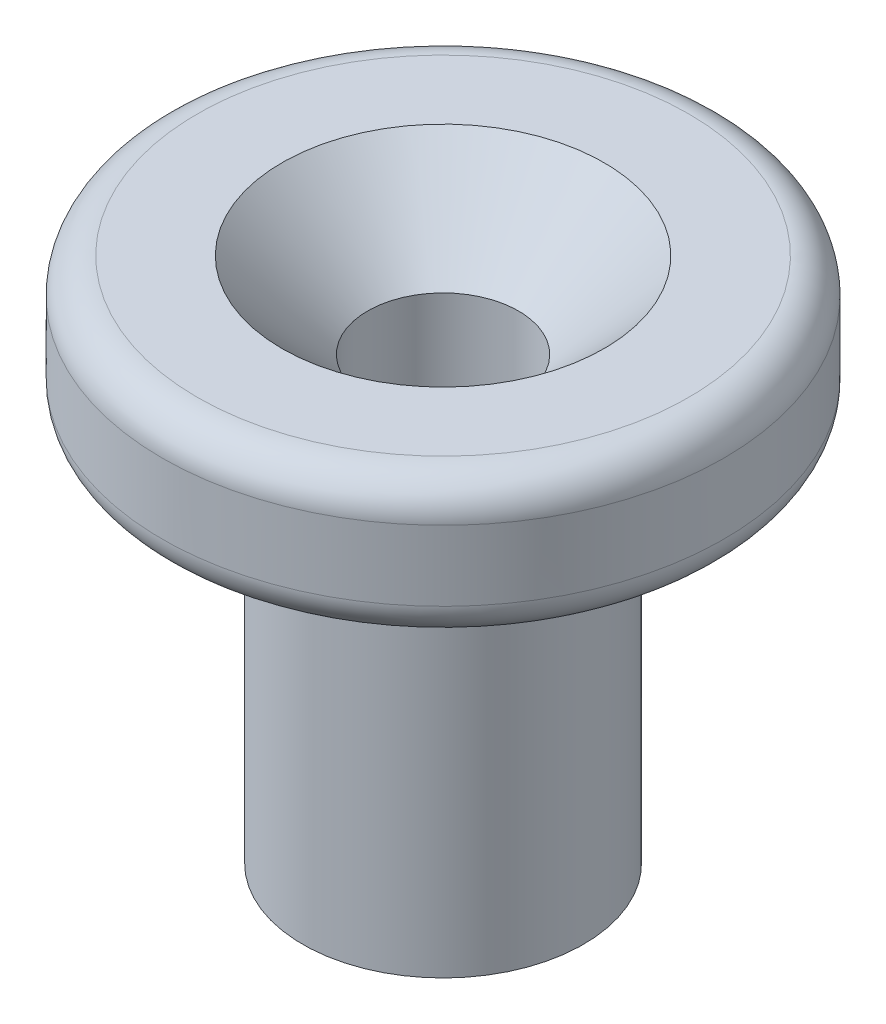
SolidWorks part; units mm, degrees
ref_plane "Front Plane" through (0, 0, 0) normal (0, 0, 1) x (1, 0, 0)
ref_plane "Top Plane" through (0, 0, 0) normal (0, 1, 0) x (1, 0, 0)
ref_plane "Right Plane" through (0, 0, 0) normal (1, 0, 0) x (0, 0, -1)
sketch "Croquis1" plane through (0, 0, 0) normal (0, 0, 1) x (1, 0, 0)
  line L0 (0, 0) -> (0, 15) construction
  line L1 (0, 15) -> (8, 15)
  line L2 (8, 15) -> (8, 11)
  line L3 (8, 11) -> (4, 11)
  line L4 (4, 11) -> (4, 0)
  line L6 (4, 0) -> (0, 0)
  line L7 (0, 0) -> (0, 15)
  dimension "D1" = 15
  dimension "D2" = 4
  dimension "D3" = 8
  dimension "D4" = 4
revolve "Revolución1" add sketch "Croquis1" angle 360 about L0
fillet "Redondeo1" radius 1 3 edges at (0, 11, -8) (0, 15, -8) (0, 11, -4)
hole_wizard "Avellanado para tornillo con cabeza avellanada de clavija hexagonal de M41" positions "Croquis2" profile "Croquis3" countersink size "M4" standard "DIN" end condition through all
sketch "Croquis2" plane through (0, 15, 0) normal (0, 1, 0) x (1, 0, 0)
  point P0 (0, 0)
sketch "Croquis3" plane through (0, 15, 0) normal (1, 0, 0) x (0, 0, 1)
  line L0 (0, 0) -> (0, 15)
  line L1 (0, 15) -> (2.15, 15)
  line L2 (2.15, 15) -> (2.15, 2.44)
  line L3 (2.15, 2.44) -> (4.59, 0)
  line L5 (4.59, 0) -> (0, 0)
  line L6 (-2.15, 2.44) -> (-4.59, 0) construction
  line L11 (0, -6.35) -> (0, 107.95) construction
  dimension "Diámetro de taladro hasta el siguiente" = 4.3
  dimension "Profundidad de taladro hasta el siguiente" = 15
  dimension "Diámetro de avellanado cercano" = 9.18
  dimension "Ángulo de avellanado cercano" = 90
